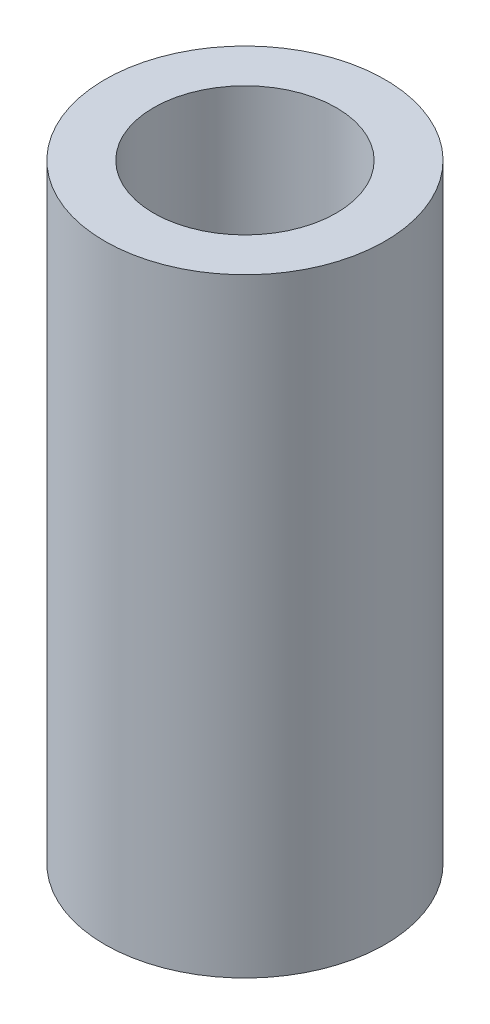
SolidWorks part; units mm, degrees
ref_plane "前视基准面" through (0, 0, 0) normal (0, 0, 1) x (1, 0, 0)
ref_plane "上视基准面" through (0, 0, 0) normal (0, 1, 0) x (1, 0, 0)
ref_plane "右视基准面" through (0, 0, 0) normal (1, 0, 0) x (0, 0, -1)
sketch "草图1" plane through (0, 0, 0) normal (0, 1, 0) x (1, 0, 0)
  circle A0 centre (0, 0) radius 1.5
  circle A1 centre (0, 0) radius 2.3
  dimension "D1" = 4.6
  dimension "D2" = 3
extrude "凸台-拉伸1" add sketch "草图1" along normal blind 10
